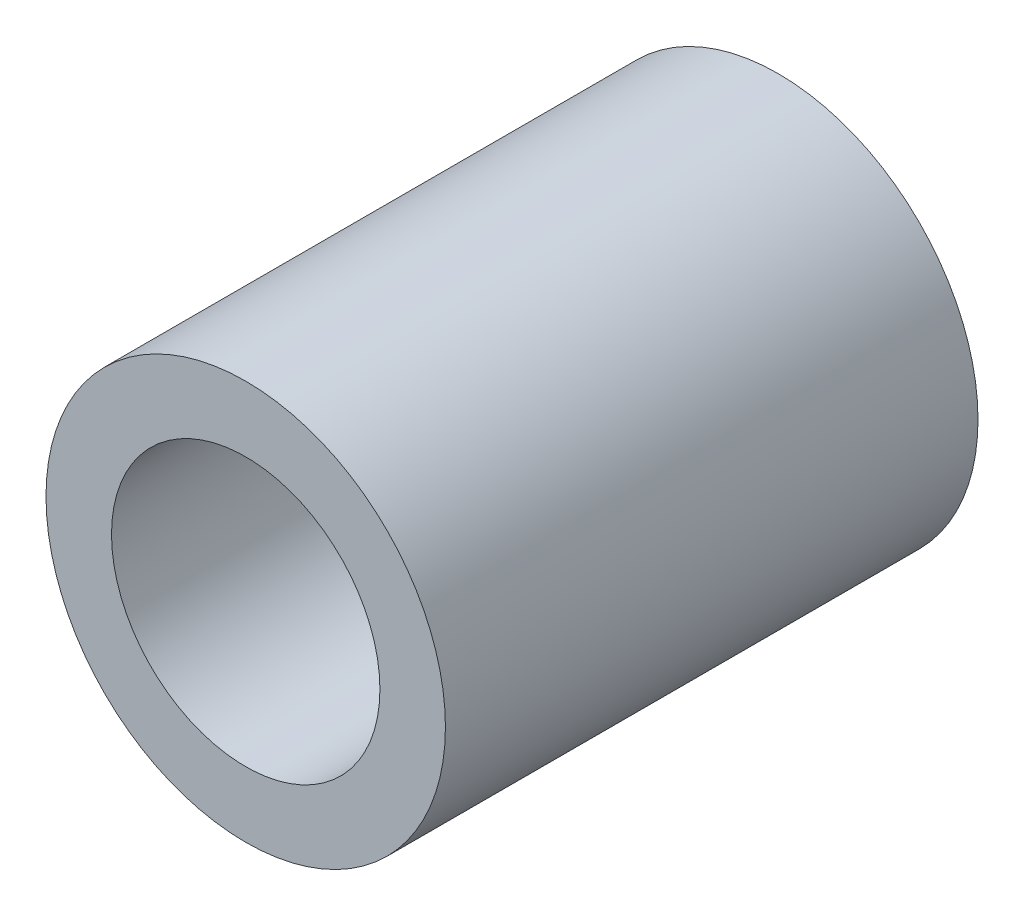
SolidWorks part; units mm, degrees
ref_plane "Front Plane" through (0, 0, 0) normal (0, 0, 1) x (1, 0, 0)
ref_plane "Top Plane" through (0, 0, 0) normal (0, 1, 0) x (1, 0, 0)
ref_plane "Right Plane" through (0, 0, 0) normal (1, 0, 0) x (0, 0, -1)
sketch "Sketch1" plane through (0, 0, 0) normal (0, 0, 1) x (1, 0, 0)
  circle A0 centre (0, 0) radius 4.7625
  circle A1 centre (0, 0) radius 3.2004
  dimension "D1" = 9.525
  dimension "ID" = 6.4008
extrude "Extrude1" add sketch "Sketch1" along normal mid plane 12.7
sketch "Sketch2" plane through (0, 0, 0) normal (1, 0, 0) x (0, 0, -1)
  line L0 (-6.35, -3.2004) -> (6.35, -3.2004) construction
  line L3 (6.35, 3.2004) -> (-6.35, 3.2004) construction
  line L5 (-6.35, -3.2004) -> (6.35, -3.2004)
  line L6 (6.35, 3.2004) -> (-6.35, 3.2004)
sketch "Sketch4" plane through (0, 0, 6.35) normal (0, 0, 1) x (1, 0, 0)
  line L0 (0, 0) -> (-2.263, 2.263)
  line L1 (0, -17.4625) -> (0, 17.4625) construction
  circle A0 centre (0, 0) radius 3.2004 construction
  dimension "D1" = 45
